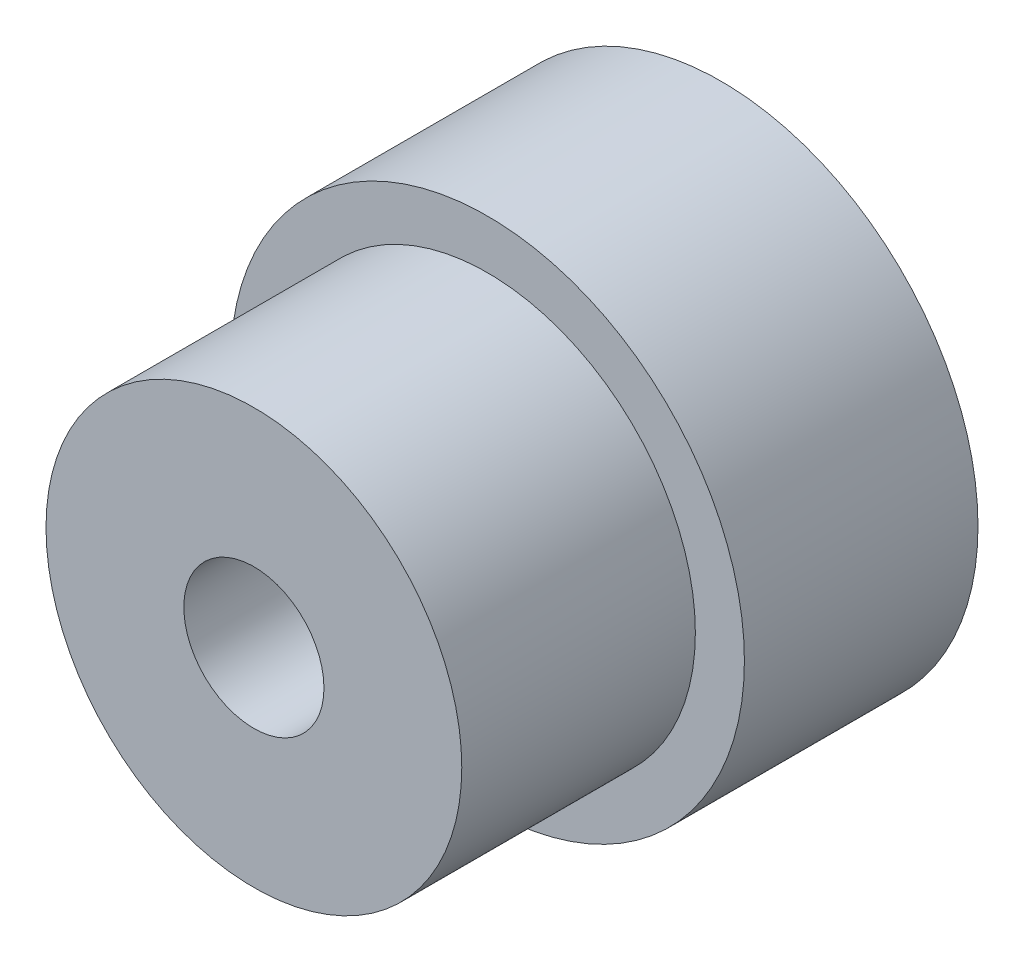
SolidWorks part; units mm, degrees
ref_plane "前视基准面" through (0, 0, 0) normal (0, 0, 1) x (1, 0, 0)
ref_plane "上视基准面" through (0, 0, 0) normal (0, 1, 0) x (1, 0, 0)
ref_plane "右视基准面" through (0, 0, 0) normal (1, 0, 0) x (0, 0, -1)
sketch "草图1" plane through (0, 0, 0) normal (0, 0, 1) x (1, 0, 0)
  circle A0 centre (0, 0) radius 5.5
  dimension "D1" = 11
extrude "凸台-拉伸1" add sketch "草图1" along normal blind 5
sketch "草图2" plane through (0, 0, 5) normal (0, 0, 1) x (1, 0, 0)
  circle A0 centre (0, 0) radius 4.45
  dimension "D1" = 8.9
extrude "凸台-拉伸2" add sketch "草图2" along normal blind 5
sketch "草图3" plane through (0, 0, 10) normal (0, 0, 1) x (1, 0, 0)
  circle A0 centre (0, 0) radius 1.5
  dimension "D1" = 3
extrude "切除-拉伸1" cut sketch "草图3" against normal through all
